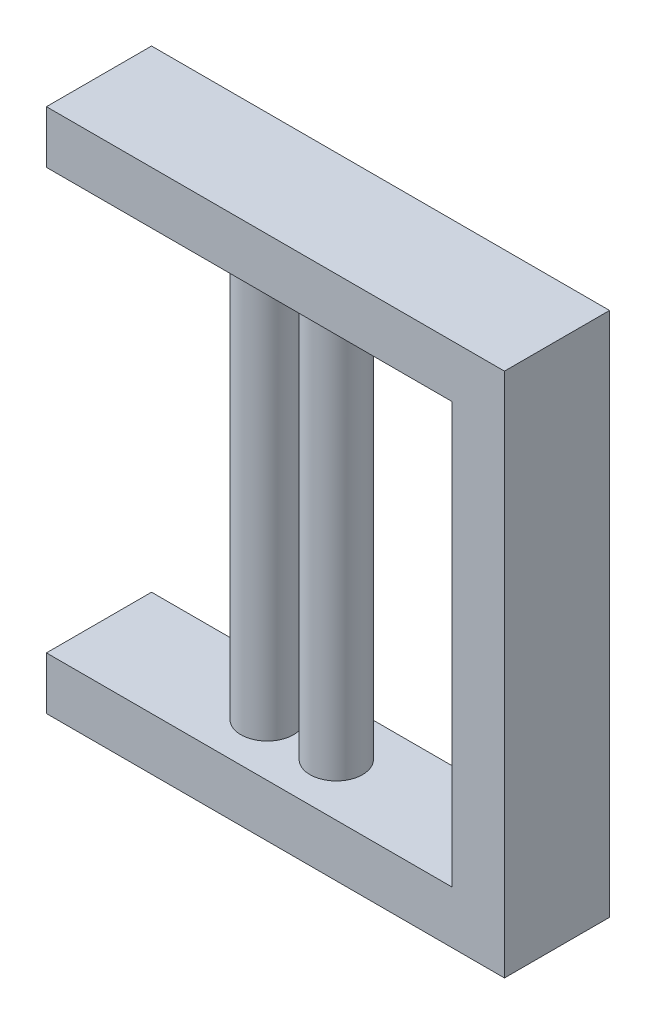
SolidWorks part; units mm, degrees
ref_plane "Front Plane" through (0, 0, 0) normal (0, 0, 1) x (1, 0, 0)
ref_plane "Top Plane" through (0, 0, 0) normal (0, 1, 0) x (1, 0, 0)
ref_plane "Right Plane" through (0, 0, 0) normal (1, 0, 0) x (0, 0, -1)
sketch "Sketch1" plane through (0, 0, 0) normal (0, 0, 1) x (1, 0, 0)
  line L0 (0, 0) -> (97.98, 0)
  line L1 (97.98, 0) -> (97.98, 101.6)
  line L2 (97.98, 101.6) -> (0, 101.6)
  line L3 (0, 101.6) -> (0, 114.3)
  line L4 (0, 114.3) -> (110.68, 114.3)
  line L5 (110.68, 114.3) -> (110.68, -12.7)
  line L6 (110.68, -12.7) -> (0, -12.7)
  line L7 (0, -12.7) -> (0, 0)
  dimension "D1" = 101.6
  dimension "D2" = 12.7
  dimension "D3" = 12.7
  dimension "D4" = 12.7
extrude "Boss-Extrude1" add sketch "Sketch1" along normal blind 25.4
sketch "Sketch2" plane through (0, 0, 0) normal (0, 1, 0) x (1, 0, 0)
  line L0 (97.98, -25.4) -> (0, -25.4) construction
  circle A0 centre (40.64, -12.7) radius 6.35
  circle A1 centre (57.34, -12.7) radius 6.35
  point P5 (48.99, -25.4)
  point P6 (-96.7342, 187.9689)
  dimension "D1" = 12.7
  dimension "D2" = 12.7
  dimension "D3" = 16.7
  dimension "D4" = 8.35
  dimension "D5" = 12.7
  dimension "D6" = 12.7
extrude "Boss-Extrude2" add sketch "Sketch2" along normal blind 101.6
